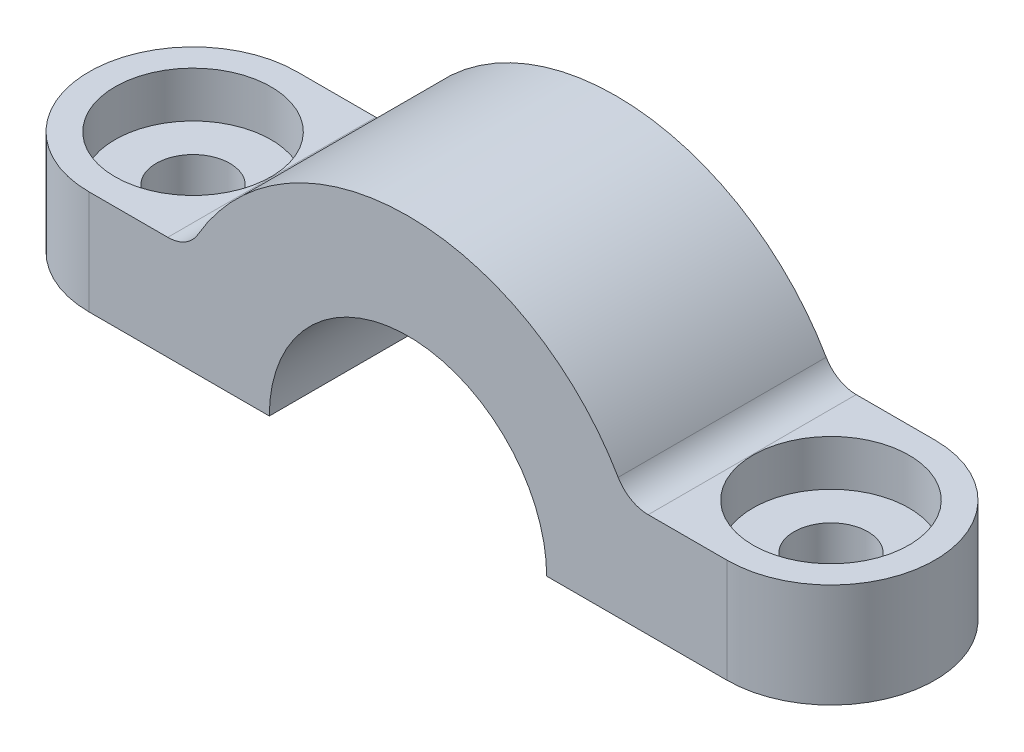
SolidWorks part; units mm, degrees
material "Plain Carbon Steel"
ref_plane "Front" through (0, 0, 0) normal (0, 0, 1) x (1, 0, 0)
ref_plane "Top" through (0, 0, 0) normal (0, 1, 0) x (1, 0, 0)
ref_plane "Right" through (0, 0, 0) normal (1, 0, 0) x (0, 0, -1)
sketch "Sketch1" plane through (0, 0, 0) normal (0, 0, 1) x (1, 0, 0)
  line L0 (-22.225, 0) -> (-12.7, 0)
  line L1 (12.7, 0) -> (22.225, 0)
  arc A0 (-22.225, 0) -> (22.225, 0) centre (0, 0) cw
  arc A1 (12.7, 0) -> (-12.7, 0) centre (0, 0) ccw
  dimension "D1" = 25.4
  dimension "D2" = 44.45
extrude "Boss-Extrude1" add sketch "Sketch1" along normal mid plane 19.05
sketch "Sketch2" plane through (0, 0, 0) normal (0, -1, 0) x (1, 0, 0)
  line L0 (-12.7, -9.525) -> (-29.21, -9.525)
  line L1 (-22.225, -9.525) -> (22.225, -9.525) construction
  line L2 (-22.225, -9.525) -> (-12.7, -9.525) construction
  line L3 (-29.21, 9.525) -> (-12.7, 9.525)
  line L4 (-12.7, 9.525) -> (-12.7, -9.525)
  line L5 (0, 0) -> (0, 19.2655) construction
  line L6 (12.7, 9.525) -> (12.7, -9.525)
  line L7 (29.21, 9.525) -> (12.7, 9.525)
  line L8 (12.7, -9.525) -> (29.21, -9.525)
  arc A0 (-29.21, -9.525) -> (-29.21, 9.525) centre (-29.21, 0) cw
  arc A1 (29.21, -9.525) -> (29.21, 9.525) centre (29.21, 0) ccw
  dimension "D1" = 29.21
extrude "Boss-Extrude2" add sketch "Sketch2" against normal blind 9.525
fillet "Fillet1" radius 3.175 2 edges at (20.0805, 9.525, 0) (-20.0805, 9.525, 0)
hole_wizard "CBORE for 1/4 Binding Head Machine Screw1" positions "Sketch4" profile "Sketch3" counterbore size "1/4" standard "ANSI Inch" end condition through all
sketch "Sketch4" plane through (0, 9.525, 0) normal (0, 1, 0) x (1, 0, 0)
  point P0 (-29.21, 0)
  point P2 (29.21, 0)
sketch "Sketch3" plane through (-29.21, 9.525, 0) normal (1, 0, 0) x (0, 0, 1)
  line L0 (0, 0) -> (0, 9.525)
  line L1 (0, 9.525) -> (3.3782, 9.525)
  line L3 (3.3782, 9.525) -> (3.3782, 4.191)
  line L4 (3.3782, 4.191) -> (7.1437, 4.191)
  line L5 (7.1437, 4.191) -> (7.1437, 0)
  line L7 (7.1437, 0) -> (0, 0)
  line L11 (0, -6.35) -> (0, 107.95) construction
  dimension "Thru Hole Dia." = 6.7564
  dimension "Thru Hole Depth" = 9.525
  dimension "C'Bore Dia." = 14.2875
  dimension "C'Bore Depth" = 4.191
